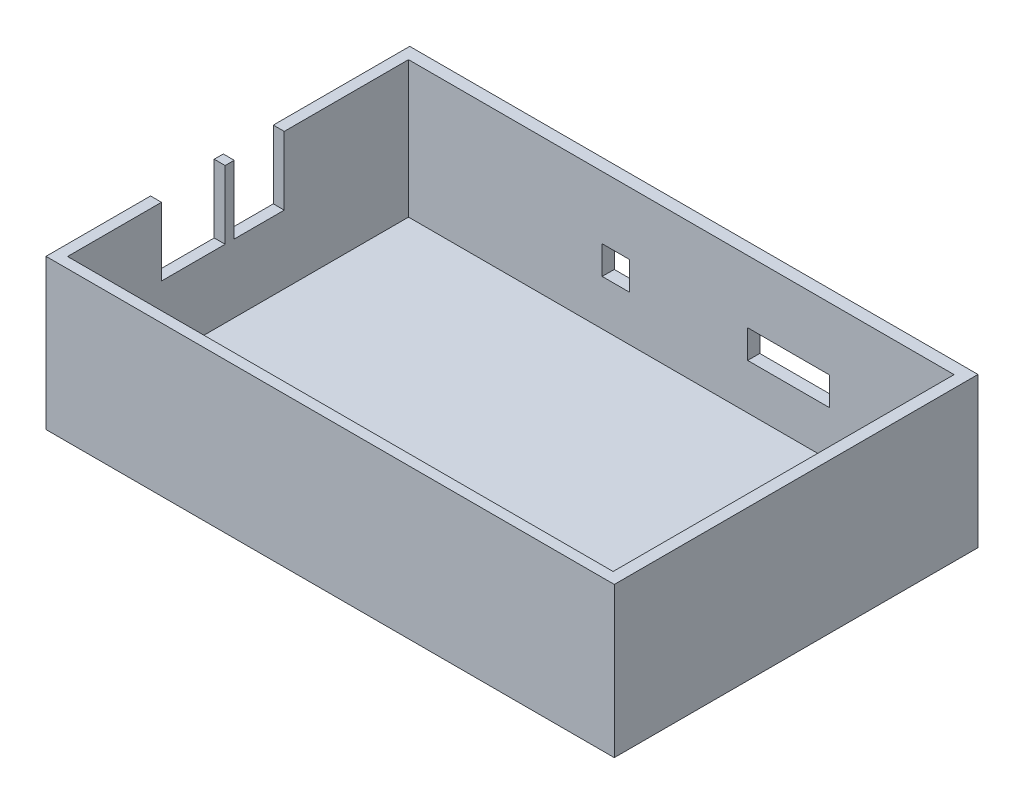
SolidWorks part; units mm, degrees
ref_plane "Front Plane" through (0, 0, 0) normal (0, 0, 1) x (1, 0, 0)
ref_plane "Top Plane" through (0, 0, 0) normal (0, 1, 0) x (1, 0, 0)
ref_plane "Right Plane" through (0, 0, 0) normal (1, 0, 0) x (0, 0, -1)
sketch "Sketch1" plane through (0, 0, 0) normal (0, 1, 0) x (1, 0, 0)
  line L1 (0, 0) -> (125, 0)
  line L2 (0, 0) -> (0, 80)
  line L3 (0, 80) -> (125, 80)
  line L4 (125, 0) -> (125, 80)
  dimension "D1" = 125
  dimension "D2" = 80
extrude "Boss-Extrude1" add sketch "Sketch1" along normal blind 33
sketch "Sketch3" plane through (0, 33, 0) normal (0, 1, 0) x (1, 0, 0)
  line L1 (2.4038, 77.336) -> (122.4038, 77.336)
  line L2 (2.4038, 77.336) -> (2.4038, 2.336)
  line L3 (2.4038, 2.336) -> (122.4038, 2.336)
  line L4 (122.4038, 77.336) -> (122.4038, 2.336)
  dimension "D1" = 120
  dimension "D2" = 75
extrude "Cut-Extrude1" cut sketch "Sketch3" against normal blind 30
sketch "Sketch6" plane through (0, 33, 0) normal (0, 1, 0) x (1, 0, 0)
  line L0 (0, 0) -> (125, 0) construction
  line L1 (-6.1813, 37) -> (7.9426, 37)
  line L2 (-6.1813, 37) -> (-6.1813, 23)
  line L3 (-6.1813, 23) -> (7.9426, 23)
  line L4 (7.9426, 37) -> (7.9426, 23)
  line L6 (-5.2121, 50) -> (7.9426, 50)
  line L7 (-5.2121, 50) -> (-5.2121, 39)
  line L8 (-5.2121, 39) -> (7.9426, 39)
  line L9 (7.9426, 50) -> (7.9426, 39)
  dimension "D1" = 14
  dimension "D2" = 23
  dimension "D3" = 11
  dimension "D4" = 39
extrude "Cut-Extrude4" cut sketch "Sketch6" against normal blind 15
sketch "Sketch7" plane through (0, 0, -80) normal (0, 0, -1) x (-1, 0, 0)
  line L0 (-125, 0) -> (0, 0) construction
  line L1 (-45, 13) -> (-51, 13)
  line L2 (-45, 13) -> (-45, 19.2312)
  line L3 (-45, 19.2312) -> (-51, 19.2312)
  line L4 (-51, 13) -> (-51, 19.2312)
  line L5 (0, 33) -> (0, 0) construction
  line L7 (-77, 13) -> (-95, 13)
  line L8 (-77, 13) -> (-77, 19.2312)
  line L9 (-77, 19.2312) -> (-95, 19.2312)
  line L10 (-95, 13) -> (-95, 19.2312)
  dimension "D1" = 13
  dimension "D2" = 6
  dimension "D3" = 45
  dimension "D4" = 18
  dimension "D5" = 77
extrude "Cut-Extrude5" cut sketch "Sketch7" against normal blind 15
